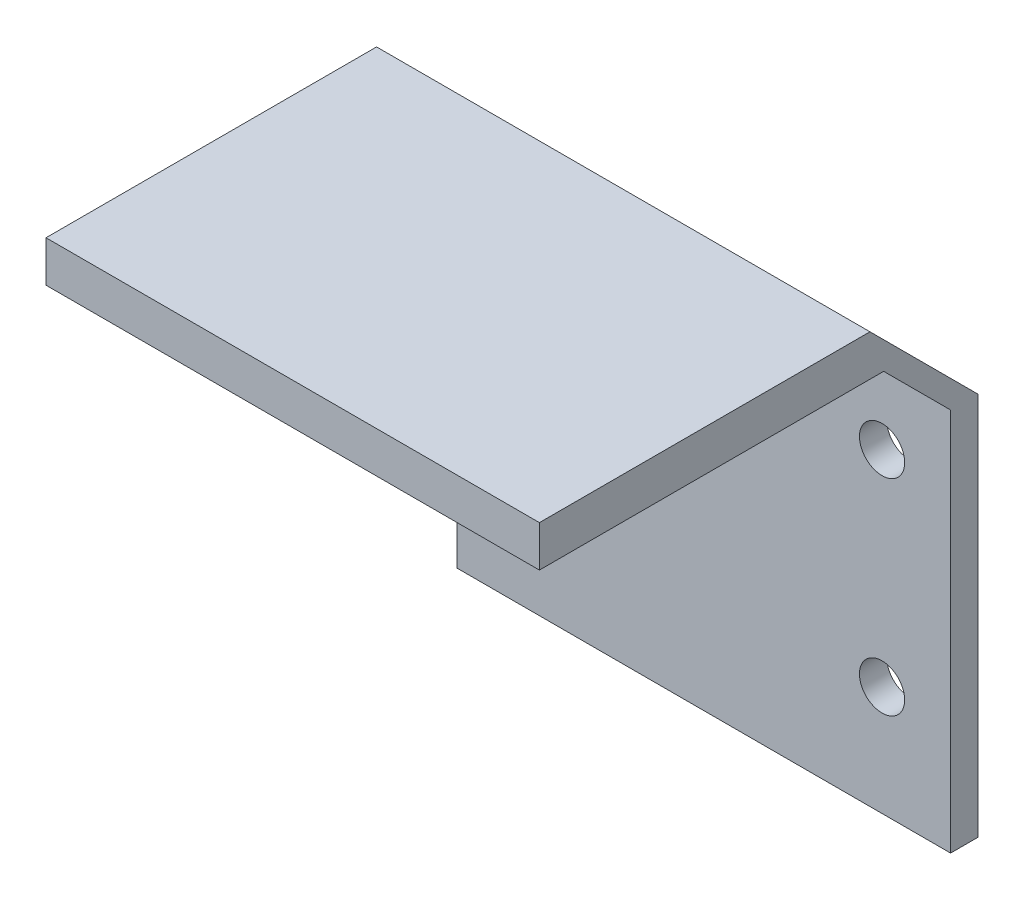
SolidWorks part; units mm, degrees
ref_plane "前视基准面" through (0, 0, 0) normal (0, 0, 1) x (1, 0, 0)
ref_plane "上视基准面" through (0, 0, 0) normal (0, 1, 0) x (1, 0, 0)
ref_plane "右视基准面" through (0, 0, 0) normal (1, 0, 0) x (0, 0, -1)
other "Configuration Table"
sketch "草图1" plane through (0, 0, 0) normal (0, 0, 1) x (1, 0, 0)
  line L1 (0, 0) -> (36, 0)
  line L2 (0, 0) -> (0, 28)
  line L3 (0, 28) -> (36, 28)
  line L4 (36, 0) -> (36, 28)
  dimension "D1" = 36
  dimension "D2" = 28
extrude "凸台-拉伸1" add sketch "草图1" along normal blind 2
sketch "草图2" plane through (36, 0, 0) normal (1, 0, 0) x (0, 0, -1)
  line L0 (-6.8821, 32.8821) -> (-2, 28)
  line L1 (-6.8821, 32.8821) -> (-32, 32.8821)
  line L2 (-32, 32.8821) -> (-32, 35.8821)
  line L3 (-32, 35.8821) -> (-7.8821, 35.8821)
  line L4 (-7.8821, 35.8821) -> (0, 28)
  line L5 (-2, 28) -> (0, 28) construction
  line L6 (-2, 0) -> (-2, 28) construction
  line L7 (0, 0) -> (0, 28) construction
  line L8 (-2, 28) -> (0, 28)
  dimension "D1" = 135
  dimension "D2" = 3
  dimension "D3" = 32
extrude "凸台-拉伸2" add sketch "草图2" against normal blind 36
sketch "草图3" plane through (0, 0, 2) normal (0, 0, 1) x (1, 0, 0)
  line L0 (36, 28) -> (0, 28) construction
  line L1 (36, 0) -> (36, 28) construction
  circle A0 centre (31, 23) radius 1.65
  circle A3 centre (6, 23) radius 1.65
  circle A4 centre (6, 8) radius 1.65
  circle A5 centre (31, 8) radius 1.65
  dimension "D1" = 3.3
  dimension "D2" = 5
  dimension "D3" = 5
  dimension "D6" = 15
  dimension "D4" = 2
  dimension "D5" = 2
extrude "切除-拉伸1" cut sketch "草图3" against normal blind 4
